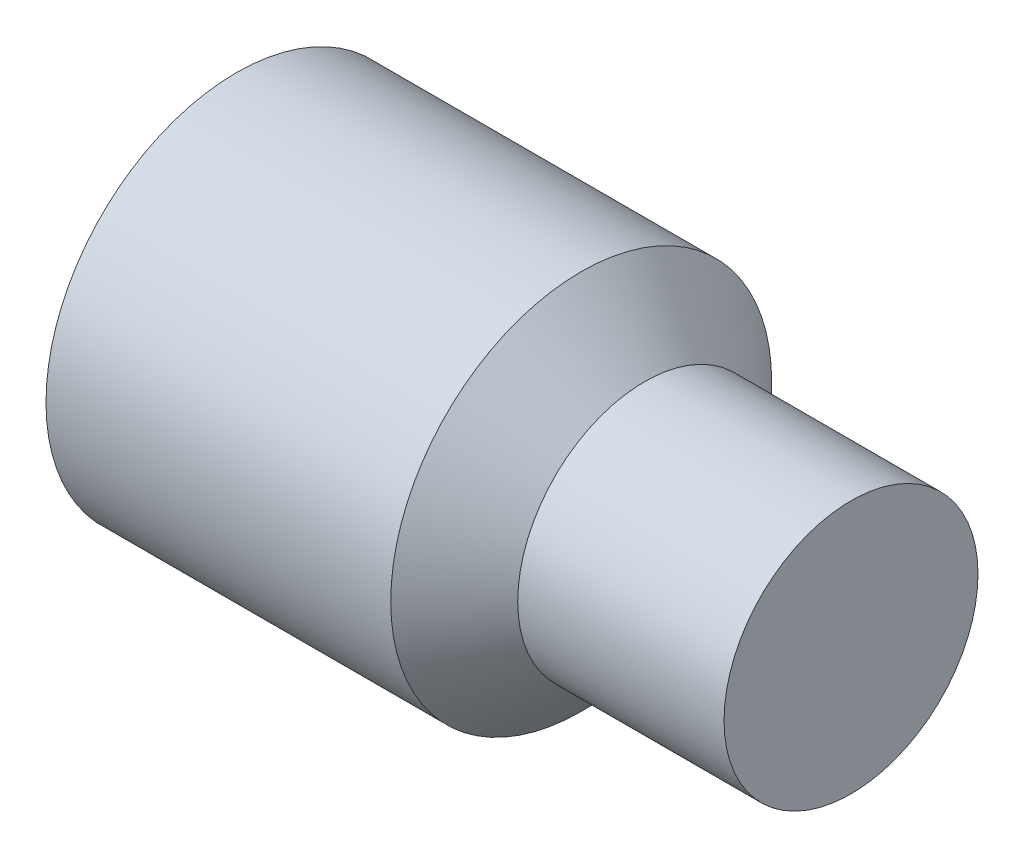
SolidWorks part; units mm, degrees
revolve "BaseBody" add sketch "BodySke" angle 360 about L5
sketch "BodySke" plane through (0, 0, 0) normal (0, 0, 1) x (1, 0, 0)
  line L0 (0, 0) -> (0, 2.4455)
  line L1 (0, 2.4455) -> (0.3201, 3)
  line L2 (0.3201, 3) -> (5.75, 3)
  line L3 (5.75, 3) -> (6.75, 2)
  line L4 (10, 0) -> (0, 0)
  line L5 (-12.7, 0) -> (88.9, 0) construction
  line L6 (6.75, 2) -> (10, 2)
  line L7 (10, 2) -> (10, 0)
  line L8 (0, -2.4455) -> (0.3201, -3) construction
  line L9 (6.75, -2) -> (10, -2) construction
  line L10 (0.5, 15.875) -> (0.5, -3.175) construction
  dimension "Diameter" = 6
  dimension "Drive_ch_ang" = 60
  dimension "Minor_dia" = 4.891
  dimension "Dog_dia" = 4
  dimension "D1" = 45
  dimension "Advance" = 1
cosmetic thread "ThreadCosmetic" parameters "Thread_minor"=4.891
ref_plane "Plane1" through (0, 0, 0) normal (0, 0, 1) x (1, 0, 0)
ref_plane "Plane2" through (0, 0, 0) normal (0, 1, 0) x (1, 0, 0)
ref_plane "Plane3" through (0, 0, 0) normal (1, 0, 0) x (0, 0, -1)
sketch "Sketch2" plane through (0, 0, 0) normal (-1, 0, 0) x (0, 0, 1)
  line L0 (0.866, 1.5) -> (-0.866, 1.5)
  line L1 (-0.866, 1.5) -> (-1.7321, 0)
  line L2 (0.866, 1.5) -> (1.7321, 0)
  line L3 (0.866, -1.5) -> (1.7321, 0)
  line L4 (0.866, -1.5) -> (-0.866, -1.5)
  line L5 (-0.866, -1.5) -> (-1.7321, 0)
  dimension "Hex_size" = 3
  dimension "D2" = 1.5
  dimension "D3" = 1.5
extrude "Hex" cut sketch "Sketch2" against normal blind 3.5
sketch "ThdSchSke" plane through (0, 0, 0) normal (0, 0, 1) x (1, 0, 0)
  line L0 (0.3201, -2.4455) -> (-0.0681, -3)
  line L1 (0.3201, -2.4455) -> (0.7084, -3)
  line L2 (0.7084, -3) -> (0.7084, -3.75)
  line L3 (-3.175, 0) -> (5.1513, 0) construction
  line L4 (0.3201, 3) -> (0.3201, -3) construction
  line L5 (0.7084, -3.75) -> (-0.0681, -3.75)
  line L6 (-0.0681, -3.75) -> (-0.0681, -3)
  dimension "Thread_minor" = 4.891
  dimension "Diameter" = 6
revolve "ThreadSchematic" [suppressed] cut sketch "ThdSchSke" angle 360 about L3
pattern_linear "ThdSchPat" [suppressed]
equation "\"D2@Sketch2\" = \"Hex_size@Sketch2\" / 2"
equation "\"D3@Sketch2\" = \"Hex_size@Sketch2\" / 2"
equation "\"Thread_minor@ThreadCosmetic\" = \"Minor_dia@BodySke\""
equation "\"Thread_minor@ThdSchSke\" = \"Thread_minor@ThreadCosmetic\""
equation "\"Diameter@ThdSchSke\" = \"Diameter@BodySke\""
equation "\"Overcut@ThdSchSke\" = \"Diameter@BodySke\" * 1.25"
equation "\"Num_threads@ThdSchPat\" = int( (\"Length@BodySke\" - ( ( ( \"Diameter@BodySke\" - \"Minor_dia@BodySke\" ) * 0.5 ) / tan( \"Drive_ch_ang@BodySke\" * 0.017453292 ) ) - \"Dog_len@BodySke\" ) / \"Advance@BodySke\" + 0.999 )  + 1"
equation "\"Advance@ThdSchPat\" = (\"Length@BodySke\" - ( ( ( \"Diameter@BodySke\" - \"Minor_dia@BodySke\" ) * 0.5 ) / tan( \"Drive_ch_ang@BodySke\" * 0.017453292 ) ) - \"Dog_len@BodySke\" ) /  (\"Num_threads@ThdSchPat\" - 1) 'relax it"
equation "\"Num_threads@ThdSchPat\" = \"Num_threads@ThdSchPat\" - sgn( \"Num_threads@ThdSchPat\" - 1) '---chamfered tips only---"
